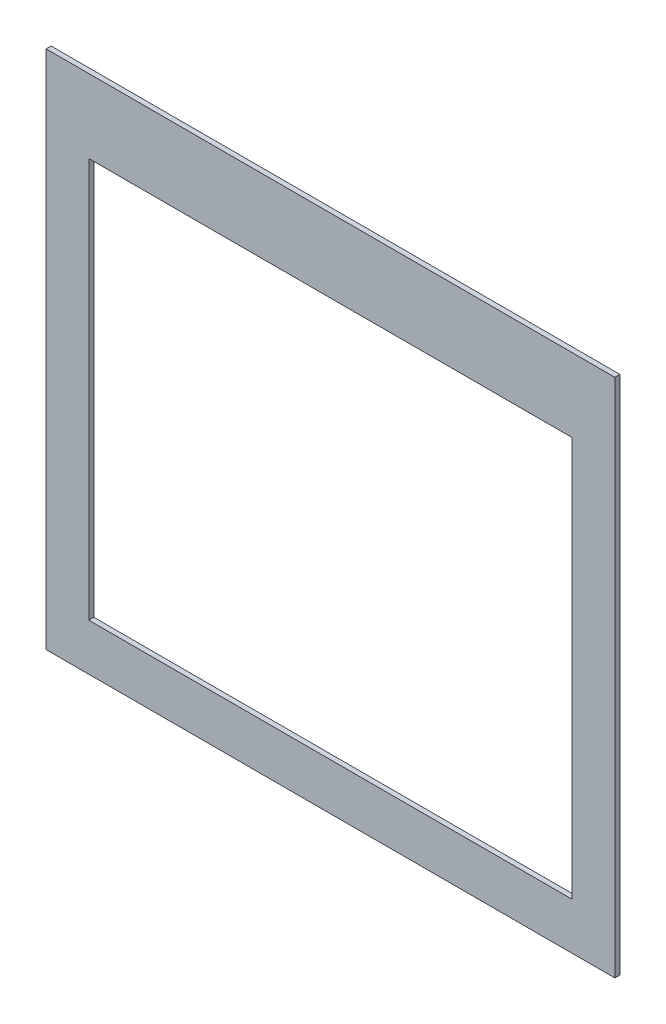
SolidWorks part; units mm, degrees
ref_plane "Piano frontale" through (0, 0, 0) normal (0, 0, 1) x (1, 0, 0)
ref_plane "Piano superiore" through (0, 0, 0) normal (0, 1, 0) x (1, 0, 0)
ref_plane "Piano destro" through (0, 0, 0) normal (1, 0, 0) x (0, 0, -1)
sketch "Schizzo1" plane through (0, 0, 0) normal (0, 0, 1) x (1, 0, 0)
  line L1 (170, -155.5) -> (-170, -155.5)
  line L2 (170, -155.5) -> (170, 155.5)
  line L3 (170, 155.5) -> (-170, 155.5)
  line L4 (-170, -155.5) -> (-170, 155.5)
  line L5 (170, -155.5) -> (-170, 155.5) construction
  line L6 (170, 155.5) -> (-170, -155.5) construction
  line L7 (144.5, -127.5) -> (-144.5, -127.5)
  line L8 (144.5, -127.5) -> (144.5, 111.5)
  line L9 (144.5, 111.5) -> (-144.5, 111.5)
  line L10 (-144.5, -127.5) -> (-144.5, 111.5)
  line L11 (144.5, -127.5) -> (-144.5, 111.5) construction
  line L12 (144.5, 111.5) -> (-144.5, -127.5) construction
  point P0 (0, 0)
  point P6 (0, -8)
  dimension "D1" = 311
  dimension "D2" = 340
  dimension "D3" = 44
  dimension "D4" = 28
  dimension "D5" = 25.5
  dimension "D6" = 25.5
extrude "Estrusione-Estrusione1" add sketch "Schizzo1" along normal blind 3
